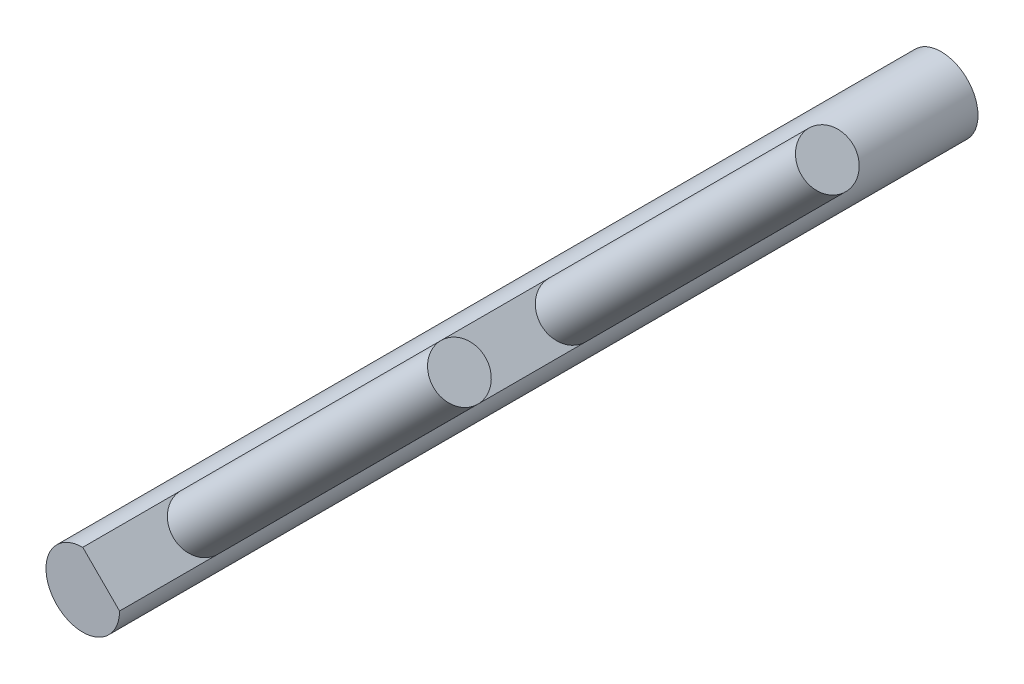
SolidWorks part; units mm, degrees
ref_plane "Plan de face" through (0, 0, 0) normal (0, 0, 1) x (1, 0, 0)
ref_plane "Plan de dessus" through (0, 0, 0) normal (0, 1, 0) x (1, 0, 0)
ref_plane "Plan de droite" through (0, 0, 0) normal (1, 0, 0) x (0, 0, -1)
sketch "Esquisse1" plane through (0, 0, 0) normal (0, 0, 1) x (1, 0, 0)
  circle A0 centre (0, 0) radius 3
extrude "Boss.-Extru.1" add sketch "Esquisse1" along normal blind 15
sketch "Esquisse2" plane through (0, 0, 0) normal (0, 0, -1) x (-1, 0, 0)
  circle A0 centre (0, 0) radius 2.5
extrude "Enlèv. mat.-Extru.1" cut sketch "Esquisse2" against normal blind 5
sketch "Esquisse3" plane through (0, 0, 15) normal (0, 0, 1) x (1, 0, 0)
  line L0 (0, 3) -> (3, 0)
  arc A0 (0, 3) -> (3, 0) centre (0, 0) ccw
  circle A1 centre (0, 0) radius 3 construction
extrude "Boss.-Extru.2" add sketch "Esquisse3" along normal blind 55
sketch "Esquisse4" plane through (1.5, 1.5, 0) normal (0.7071, 0.7071, 0) x (0, 0, -1)
  line L0 (-70, -2.1213) -> (-70, 2.1213) construction
  circle A0 centre (-62, 0) radius 2.1213
  circle A1 centre (-32, 0) radius 2.1213
  dimension "D1" = 8
  dimension "D2" = 38
ref_plane "Plan1" through (1.5, 1.5, 0) normal (0.7071, 0.7071, 0) x (0.7071, -0.7071, 0)
extrude "Boss.-Extru.3" add sketch "Esquisse4" along normal blind 30 contours A1 | A0
